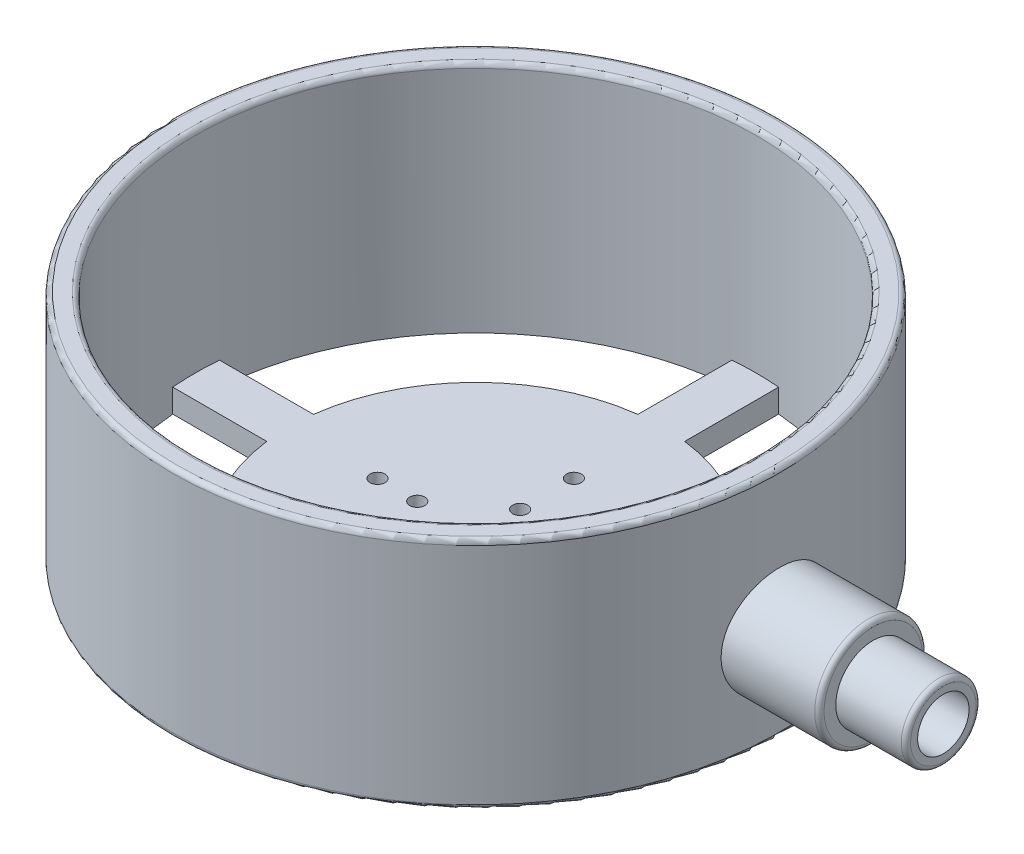
SolidWorks part; units mm, degrees
ref_plane "Front Plane" through (0, 0, 0) normal (0, 0, 1) x (1, 0, 0)
ref_plane "Top Plane" through (0, 0, 0) normal (0, 1, 0) x (1, 0, 0)
ref_plane "Right Plane" through (0, 0, 0) normal (1, 0, 0) x (0, 0, -1)
sketch "Sketch1" plane through (0, 0, 0) normal (0, 1, 0) x (1, 0, 0)
  circle A0 centre (0, 0) radius 60
  circle A2 centre (0, 0) radius 65
extrude "Boss-Extrude2" add sketch "Sketch1" along normal blind 50
sketch "Sketch2" plane through (0, 0, 0) normal (0, -1, 0) x (-1, 0, 0)
  line L1 (0, -60) -> (-5, -60)
  line L2 (-5, -60) -> (-5, 60)
  line L3 (-5, 60) -> (0, 60)
  line L4 (0, 60) -> (5, 60)
  line L5 (5, 60) -> (5, -60)
  line L6 (5, -60) -> (0, -60)
  line L7 (-60, 0) -> (-60, 5)
  line L8 (-60, 5) -> (60, 5)
  line L9 (60, 5) -> (60, 0)
  line L10 (60, 0) -> (60, -5)
  line L11 (60, -5) -> (-60, -5)
  line L12 (-60, -5) -> (-60, 0)
  circle A0 centre (0, 0) radius 60 construction
  circle A1 centre (0, 0) radius 40
extrude "Boss-Extrude4" add sketch "Sketch2" against normal blind 5 contours L2 L3 L4 L5 L6 L1 | L11 L12 L7 L8 L9 L10 | A1
sketch "Sketch9" plane through (0, 0, 0) normal (0, 0, 1) x (1, 0, 0)
  line L0 (0, 0) -> (0, 20) construction
  line L1 (0, 20) -> (100, 20) construction
  line L2 (100, 12) -> (100, 14.5)
  line L3 (100, 14.5) -> (63, 14.5)
  line L4 (100, 12) -> (85, 12)
  line L5 (85, 12) -> (85, 8.5)
  line L6 (85, 8.5) -> (63, 8.5)
  line L7 (63, 14.5) -> (63, 8.5)
sketch "Sketch15" plane through (0, 0, 0) normal (0, -1, 0) x (-1, 0, 0)
  line L0 (0, 0) -> (0, -9.5)
  line L1 (0, 0) -> (0, 9.5)
  line L2 (0, 0) -> (-12.5, 0)
  line L3 (0, 0) -> (12.5, 0)
  line L4 (0, 0) -> (0, -21)
  line L5 (0, 0) -> (-21, 0)
  line L6 (0, 0) -> (0, 21)
  line L7 (0, 0) -> (21, 0)
  circle A0 centre (0, -9.5) radius 1.6
  circle A1 centre (-12.5, 0) radius 1.6
  circle A2 centre (0, 9.5) radius 1.6
  circle A3 centre (12.5, 0) radius 1.6
  circle A4 centre (0, -21) radius 1.6
  circle A5 centre (-21, 0) radius 1.6
  circle A6 centre (0, 21) radius 1.6
  circle A7 centre (21, 0) radius 1.6
extrude "Cut-Extrude7" cut sketch "Sketch15" against normal blind 10 contours A3 | A7 | A0 | A4 | A1 | A5 | A2 | A6
revolve "Revolve1" add sketch "Sketch9" angle 360 about L1
sketch "Sketch16" plane through (100, 0, 0) normal (1, 0, 0) x (0, 0, -1)
  circle A0 centre (0, 20) radius 5.5
extrude "Cut-Extrude9" cut sketch "Sketch16" against normal blind 50
fillet "Fillet1" radius 1 5 edges at (0, 50, 65) (0, 0, 65) (0, 50, 60) (85, 20, 11.5) (100, 20, 8)
